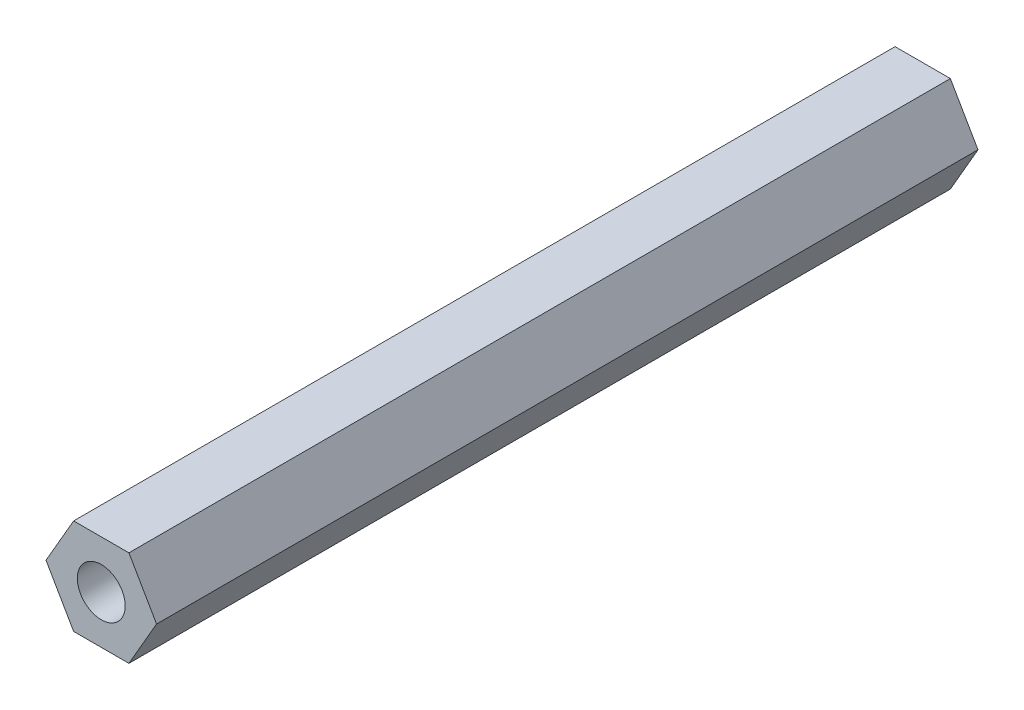
SolidWorks part; units mm, degrees
material "1060 Alloy"
ref_plane "Front Plane" through (0, 0, 0) normal (0, 0, 1) x (1, 0, 0)
ref_plane "Top Plane" through (0, 0, 0) normal (0, 1, 0) x (1, 0, 0)
ref_plane "Right Plane" through (0, 0, 0) normal (1, 0, 0) x (0, 0, -1)
sketch "Sketch1" plane through (0, 0, 0) normal (0, 0, 1) x (1, 0, 0)
  line L1 (3.6662, 6.35) -> (-3.6662, 6.35)
  line L2 (-3.6662, 6.35) -> (-7.3323, 0)
  line L3 (-7.3323, 0) -> (-3.6662, -6.35)
  line L4 (-3.6662, -6.35) -> (3.6662, -6.35)
  line L5 (3.6662, -6.35) -> (7.3323, 0)
  line L6 (7.3323, 0) -> (3.6662, 6.35)
  circle A0 centre (0, 0) radius 6.35 construction
  circle A1 centre (0, 0) radius 3.175
  dimension "D2" = 6.35
  dimension "D1" = 12.7
extrude "Boss-Extrude1" add sketch "Sketch1" along normal mid plane 108.966
